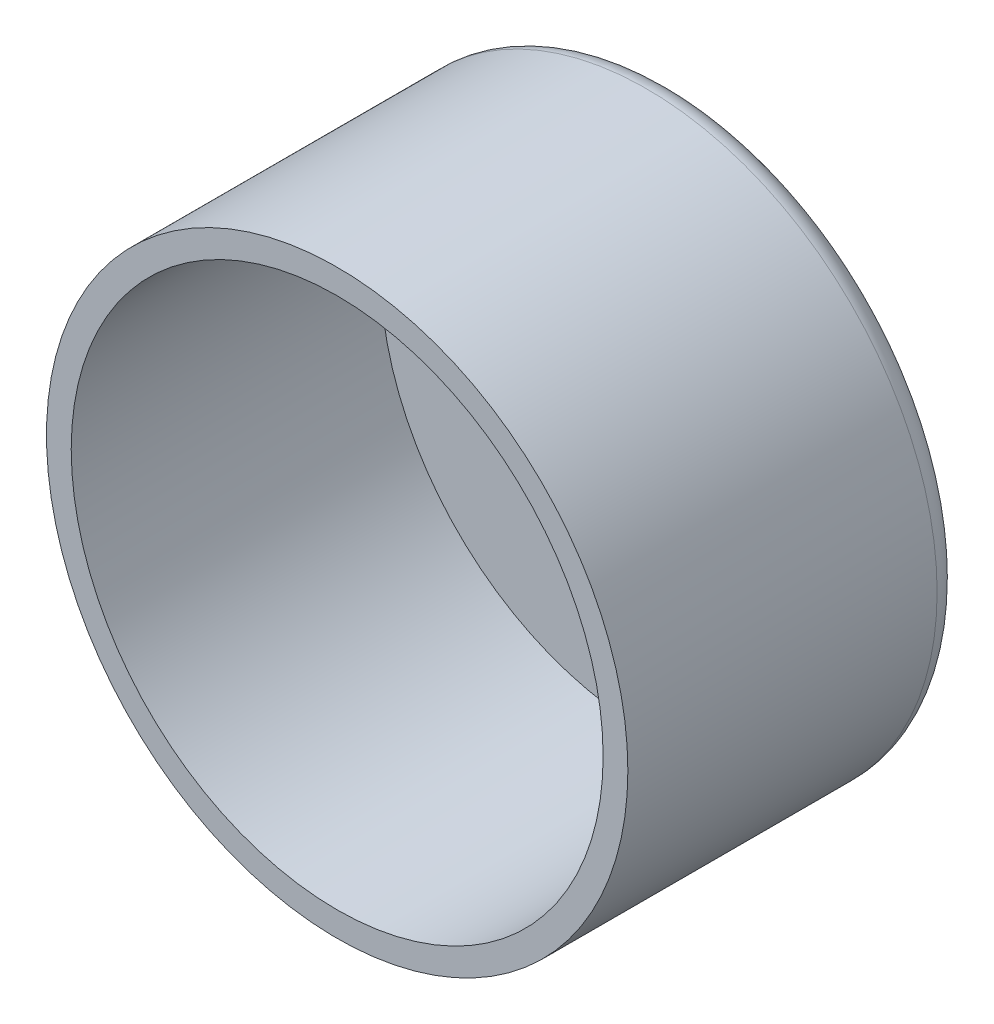
SolidWorks part; units mm, degrees
ref_plane "Front Plane" through (0, 0, 0) normal (0, 0, 1) x (1, 0, 0)
ref_plane "Top Plane" through (0, 0, 0) normal (0, 1, 0) x (1, 0, 0)
ref_plane "Right Plane" through (0, 0, 0) normal (1, 0, 0) x (0, 0, -1)
sketch "Sketch1" plane through (0, 0, 0) normal (0, 0, 1) x (1, 0, 0)
  circle A0 centre (0, 0) radius 21.5 construction
  circle A1 centre (0, 0) radius 23.5
  circle A2 centre (0, 0) radius 21 construction
  dimension "D1" = 43
  dimension "D3" = 42
  dimension "D2" = 2
extrude "Boss-Extrude1" add sketch "Sketch1" along normal blind 27
shell "Shell1" thickness 2
fillet "Fillet1" radius 2 1 edges at (23.5, 0, 0)
